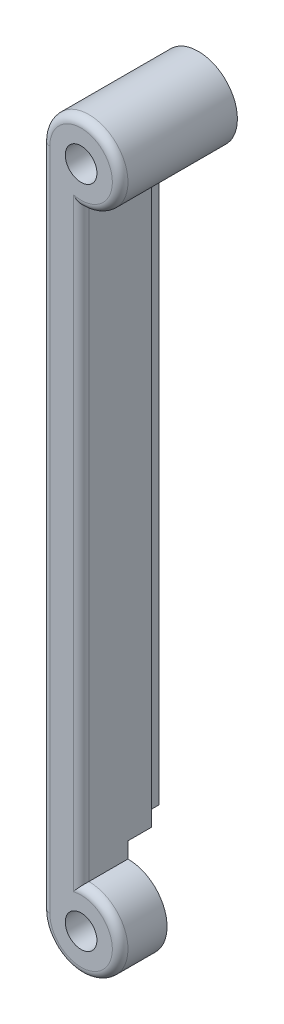
SolidWorks part; units mm, degrees
ref_plane "Front Plane" through (0, 0, 0) normal (0, 0, 1) x (1, 0, 0)
ref_plane "Top Plane" through (0, 0, 0) normal (0, 1, 0) x (1, 0, 0)
ref_plane "Right Plane" through (0, 0, 0) normal (1, 0, 0) x (0, 0, -1)
sketch "Sketch1" plane through (0, 0, 0) normal (0, 0, 1) x (1, 0, 0)
  line L0 (0, 0) -> (0, 85) construction
  line L1 (-5, 0) -> (-5, 85)
  line L3 (0, 5) -> (0, 80)
  arc A1 (0, 80) -> (-5, 85) centre (0, 85) ccw
  circle A2 centre (0, 85) radius 2.025
  circle A3 centre (0, 0) radius 2.025
  arc A4 (0, -5) -> (0, 5) centre (0, 0) ccw
  arc A5 (-5, 0) -> (0, -5) centre (0, 0) ccw
  point P3 (0, 30)
  dimension "D1" = 4.05
  dimension "D3" = 5
  dimension "D4" = 5
  dimension "D2" = 85
extrude "Boss-Extrude1" add sketch "Sketch1" along normal blind 9
sketch "Sketch2" plane through (0, 0, 9) normal (0, 0, 1) x (1, 0, 0)
  circle A0 centre (0, 85) radius 5
  circle A1 centre (0, 85) radius 2.025
  dimension "D1" = 4.05
  dimension "D2" = 10
extrude "Boss-Extrude2" add sketch "Sketch2" against normal blind 15
sketch "Sketch3" plane through (0, 0, 9) normal (0, 0, 1) x (1, 0, 0)
  line L1 (-5, 0) -> (-5, 85)
  line L3 (-2, 80.4174) -> (-2, 5)
  line L4 (-5, 85) -> (-5, 0) construction
  line L6 (-2, 5) -> (0, 5)
  line L7 (0, 5) -> (0, 80) construction
  arc A3 (-5, 0) -> (0, -5) centre (0, 0) ccw
  arc A4 (-5, 0) -> (0, 5) centre (0, 0) ccw construction
  circle A7 centre (0, 0) radius 2.025
  arc A8 (0, 5) -> (0, -5) centre (0, 0) cw
  arc A9 (-5, 0) -> (0, 5) centre (0, 0) ccw construction
  arc A10 (-5, 85) -> (-2, 80.4174) centre (0, 85) ccw
  circle A11 centre (0, 85) radius 5 construction
  dimension "D1" = 3
  dimension "D2" = 4.05
extrude "Boss-Extrude3" add sketch "Sketch3" against normal blind 12
sketch "Sketch4" plane through (0, 0, 0) normal (0, 0, -1) x (-1, 0, 0)
  line L1 (0.2377, 81.8335) -> (2.8611, 83.6226)
  line L2 (2.8611, 83.6226) -> (2.6234, 86.7891)
  line L3 (2.6234, 86.7891) -> (-0.2377, 88.1665)
  line L4 (-0.2377, 88.1665) -> (-2.8611, 86.3774)
  line L5 (-2.8611, 86.3774) -> (-2.6234, 83.2109)
  line L6 (-2.6234, 83.2109) -> (0.2377, 81.8335)
  circle A0 centre (0, 85) radius 2.75 construction
sketch "Croquis1" plane through (-5, 0, 0) normal (-1, 0, 0) x (0, 0, 1)
  line L0 (-3, 85) -> (-3, 0) construction
  line L1 (3, 7.0113) -> (-3, 7.0113)
  line L2 (3, 7.0113) -> (3, -5)
  line L3 (3, -5) -> (-3, -5)
  line L4 (-3, 7.0113) -> (-3, -5)
  dimension "D1" = 6
extrude "Cortar-Extruir3" cut sketch "Croquis1" against normal blind 10
fillet "Redondeo1" radius 1 2 edges at (-1.0215, 80.1055, 0) (-2, 43.7143, 0)
fillet "Redondeo2" radius 1 4 edges at (3.5355, 88.5355, 9) (3.5355, -3.5355, 9) (-5, 42.5, 9) (0, 42.5, 9)
